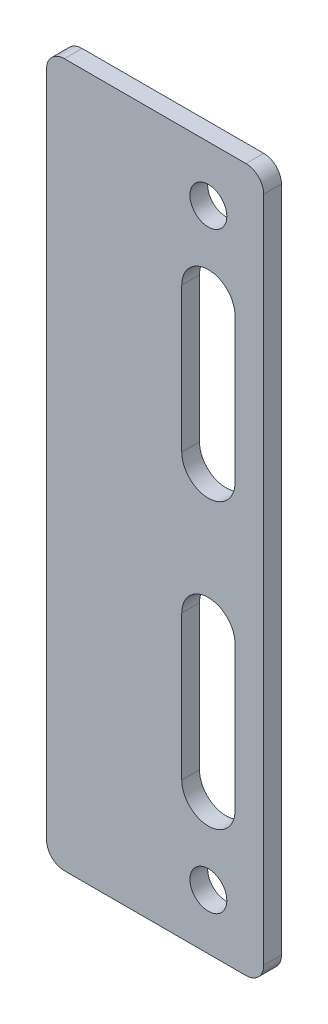
SolidWorks part; units mm, degrees
material "AISI 4130 Steel, annealed at 865C"
ref_plane "X-Y Datum" through (0, 0, 0) normal (0, 0, 1) x (1, 0, 0)
ref_plane "X-Z Datum" through (0, 0, 0) normal (0, 1, 0) x (1, 0, 0)
ref_plane "Y-Z Datum" through (0, 0, 0) normal (1, 0, 0) x (0, 0, -1)
sketch "Sketch1" plane through (0, 0, 0) normal (0, 0, 1) x (1, 0, 0)
  line L1 (9.9, -62.9) -> (-9.9, -62.9)
  line L2 (9.9, -62.9) -> (9.9, 62.9)
  line L3 (9.9, 62.9) -> (-9.9, 62.9)
  line L4 (-9.9, -62.9) -> (-9.9, 62.9)
  line L5 (0, -53) -> (0, 53) construction
  line L7 (-9.9, 62.9) -> (-28.95, 62.9)
  line L8 (-9.9, 62.9) -> (-9.9, -62.9)
  line L9 (-9.9, -62.9) -> (-28.95, -62.9)
  line L10 (-28.95, 62.9) -> (-28.95, -62.9)
  circle A0 centre (0, 53) radius 3.3
  circle A1 centre (0, -53) radius 3.3
  point P4 (0, 62.9)
  point P5 (-9.9, 0)
  point P10 (0, 0)
  dimension "D1" = 6.6
  dimension "D2" = 9.9
  dimension "D3" = 106
  dimension "D4" = 9.9
  dimension "D5" = 19.05
extrude "Boss-Extrude1" add sketch "Sketch1" along normal blind 3.175
sketch "Sketch6" plane through (0, 0, 3.175) normal (0, 0, 1) x (1, 0, 0)
  line L0 (0, 38.3375) -> (0, 12.4625) construction
  line L1 (4.7625, 38.3375) -> (4.7625, 12.4625)
  line L2 (-4.7625, 38.3375) -> (-4.7625, 12.4625)
  line L3 (0, -12.4625) -> (0, -38.3375) construction
  line L4 (4.7625, -12.4625) -> (4.7625, -38.3375)
  line L5 (-4.7625, -12.4625) -> (-4.7625, -38.3375)
  line L6 (0, 53) -> (0, 0) construction
  line L8 (9.9, 62.9) -> (-28.95, 62.9) construction
  arc A0 (4.7625, 38.3375) -> (-4.7625, 38.3375) centre (0, 38.3375) ccw
  arc A1 (-4.7625, 12.4625) -> (4.7625, 12.4625) centre (0, 12.4625) ccw
  arc A2 (4.7625, -12.4625) -> (-4.7625, -12.4625) centre (0, -12.4625) ccw
  arc A3 (-4.7625, -38.3375) -> (4.7625, -38.3375) centre (0, -38.3375) ccw
  circle A5 centre (0, 53) radius 9.9 construction
  circle A6 centre (0, 53) radius 3.3 construction
  point P3 (0, 25.4)
  point P10 (0, -25.4)
  dimension "D2" = 9.525
  dimension "D3" = 25.4
  dimension "D4" = 25.4
extrude "Cut-Extrude1" cut sketch "Sketch6" against normal through all both and the other way through all
fillet "Fillet1" radius 3.175 4 edges at (9.9, -62.9, 1.5875) (9.9, 62.9, 1.5875) (-28.95, -62.9, 1.5875) (-28.95, 62.9, 1.5875)
